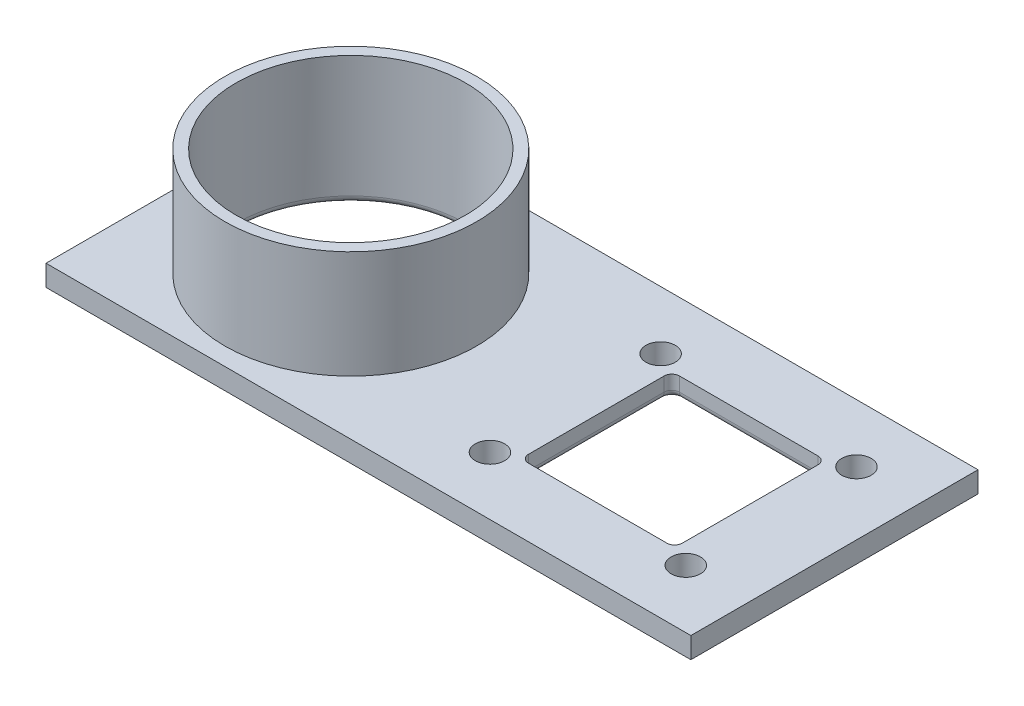
SolidWorks part; units mm, degrees
ref_plane "Alzado" through (0, 0, 0) normal (0, 0, 1) x (1, 0, 0)
ref_plane "Planta" through (0, 0, 0) normal (0, 1, 0) x (1, 0, 0)
ref_plane "Vista lateral" through (0, 0, 0) normal (1, 0, 0) x (0, 0, -1)
sketch "Croquis1" plane through (0, 0, 0) normal (0, 1, 0) x (1, 0, 0)
  line L0 (0, 0) -> (23.0489, 0) construction
  line L1 (-23.0489, -10.2629) -> (23.0489, -10.2629)
  line L2 (-23.0489, -10.2629) -> (-23.0489, 10.2629)
  line L3 (-23.0489, 10.2629) -> (23.0489, 10.2629)
  line L4 (23.0489, -10.2629) -> (23.0489, 10.2629)
  line L5 (-23.0489, -10.2629) -> (23.0489, 10.2629) construction
  line L6 (-23.0489, 10.2629) -> (23.0489, -10.2629) construction
  line L8 (4.5244, -6.1) -> (18.5244, -6.1) construction
  line L9 (4.5244, -6.1) -> (4.5244, 6.1) construction
  line L10 (4.5244, 6.1) -> (18.5244, 6.1) construction
  line L11 (18.5244, -6.1) -> (18.5244, 6.1) construction
  line L12 (4.5244, -6.1) -> (18.5244, 6.1) construction
  line L13 (4.5244, 6.1) -> (18.5244, -6.1) construction
  circle A0 centre (4.5244, 6.1) radius 1.05
  circle A1 centre (18.5244, 6.1) radius 1.05
  circle A2 centre (18.5244, -6.1) radius 1.05
  circle A3 centre (4.5244, -6.1) radius 1.05
  point P0 (0, 0)
  point P8 (11.5244, 0)
  dimension "D3" = 2.1
  dimension "D4" = 2.1
  dimension "D1" = 12.2
  dimension "D2" = 14
extrude "Saliente-Extruir1" add sketch "Croquis1" along normal blind 1.5
sketch "Croquis4" plane through (0, 1.5, 0) normal (0, 1, 0) x (1, 0, 0)
  line L0 (4.5244, 6.1) -> (18.5244, -6.1) construction
  line L2 (6.0244, -5.4) -> (17.0244, -5.4)
  line L3 (6.0244, -5.4) -> (6.0244, 5.4)
  line L4 (6.0244, 5.4) -> (17.0244, 5.4)
  line L5 (17.0244, -5.4) -> (17.0244, 5.4)
  line L6 (6.0244, -5.4) -> (17.0244, 5.4) construction
  line L7 (6.0244, 5.4) -> (17.0244, -5.4) construction
  point P4 (11.5244, 0)
  dimension "D1" = 10.8
  dimension "D2" = 11
extrude "Cortar-Extruir1" cut sketch "Croquis4" against normal blind 1.5 contours L3 L2 L5 L4
fillet "Redondeo1" radius 0.55 4 edges at (17.0244, 0.75, 5.4) (6.0244, 0.75, 5.4) (17.0244, 0.75, -5.4) (6.0244, 0.75, -5.4)
sketch "Croquis7" plane through (0, 1.5, 0) normal (0, 1, 0) x (1, 0, 0)
  line L0 (0, 0) -> (-23.0489, 0) construction
  line L1 (-23.0489, 10.2629) -> (-23.0489, -10.2629) construction
  circle A0 centre (-11.5244, 0) radius 9
  dimension "D1" = 18
extrude "Saliente-Extruir3" add sketch "Croquis7" along normal blind 7.7
sketch "Croquis8" plane through (0, 9.2, 0) normal (0, 1, 0) x (1, 0, 0)
  circle A0 centre (-11.5244, 0) radius 8.2
extrude "Cortar-Extruir3" cut sketch "Croquis8" against normal through all
fillet "Redondeo2" radius 0.5 8 edges at (16.8633, 0, 5.2389) (16.8633, 0, -5.2389) (6.1855, 0, 5.2389) (6.1855, 0, -5.2389) (11.5244, 0, 5.4) (17.0244, 0, 0) (11.5244, 0, -5.4) (6.0244, 0, 0)
fillet "Redondeo3" radius 0.5 1 edges at (-11.5244, 0, 8.2)
